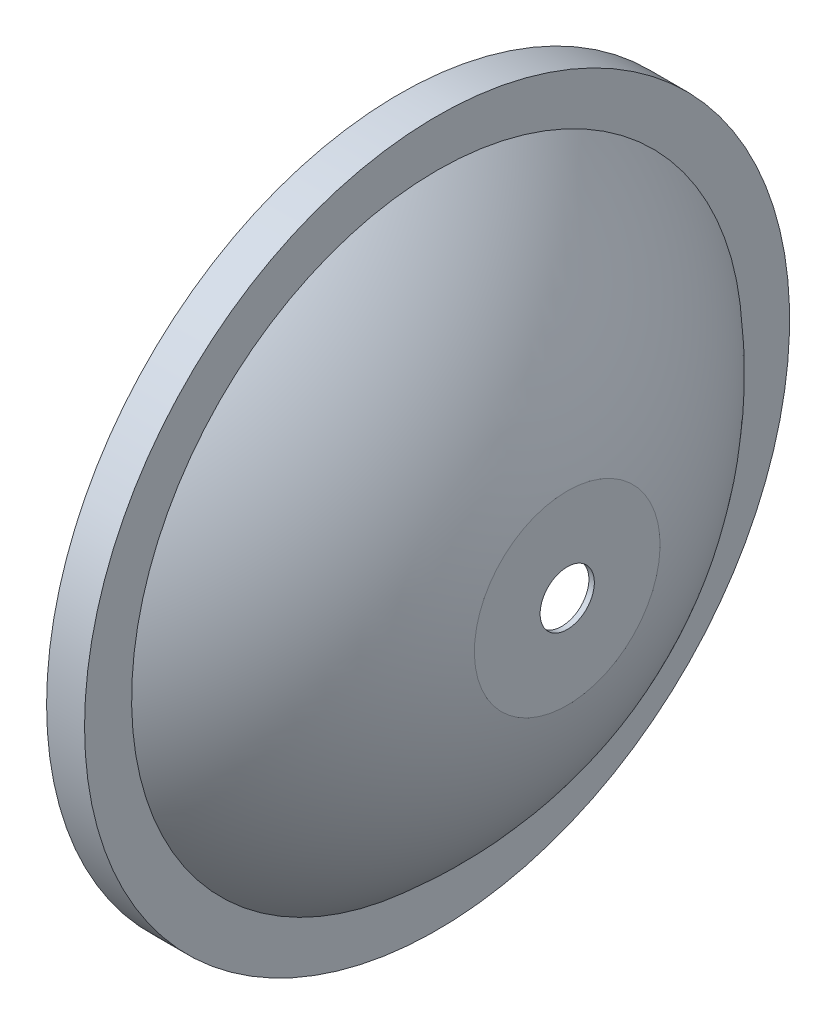
SolidWorks part; units mm, degrees
ref_plane "Front Plane" through (0, 0, 0) normal (0, 0, 1) x (1, 0, 0)
ref_plane "Top Plane" through (0, 0, 0) normal (0, 1, 0) x (1, 0, 0)
ref_plane "Right Plane" through (0, 0, 0) normal (1, 0, 0) x (0, 0, -1)
sketch "Sketch1" plane through (0, 0, 0) normal (0, 0, 1) x (1, 0, 0)
  line L0 (-81.8497, 0) -> (76.9007, 0) construction
  line L1 (-29.993, 64) -> (-23.993, 64)
  line L2 (-23.993, 64) -> (-23.993, 55.857)
  line L3 (0, 5) -> (0, 17)
  line L4 (1, 5) -> (1, 17.1177)
  line L5 (-22.993, 65) -> (-22.993, 56.3205)
  line L6 (-29.993, 65) -> (-22.993, 65)
  line L7 (-29.993, 65) -> (-29.993, 64)
  line L8 (0, 5) -> (1, 5)
  arc A0 (0, 17) -> (-23.993, 55.857) centre (-70.993, 0) ccw
  arc A1 (1, 17.1177) -> (-22.993, 56.3205) centre (-70.993, 0) ccw
  point P9 (-26.993, 64)
  dimension "D6" = 73
  dimension "D1" = 64
  dimension "D2" = 5
  dimension "D3" = 12
  dimension "D4" = 6
  dimension "D5" = 41
  dimension "D7" = 1
revolve "Revolve2" add sketch "Sketch1" angle 360 about L0
